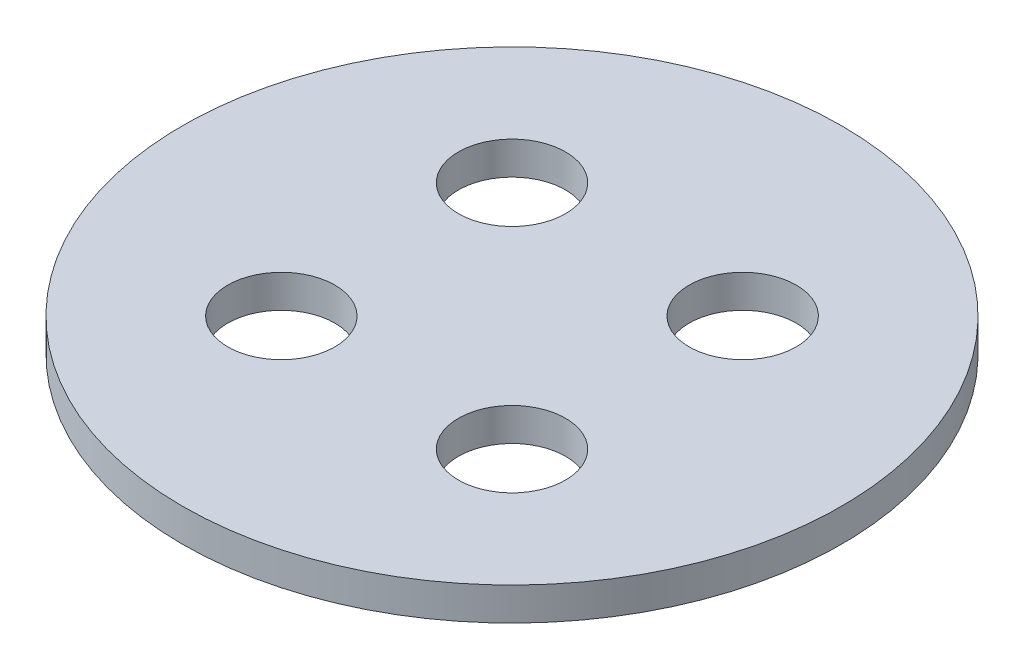
SolidWorks part; units mm, degrees
material "1023 Carbon Steel Sheet (SS)"
ref_plane "Front Plane" through (0, 0, 0) normal (0, 0, 1) x (1, 0, 0)
ref_plane "Top Plane" through (0, 0, 0) normal (0, 1, 0) x (1, 0, 0)
ref_plane "Right Plane" through (0, 0, 0) normal (1, 0, 0) x (0, 0, -1)
sketch "Sketch1" plane through (0, 0, 0) normal (0, 1, 0) x (1, 0, 0)
  line L0 (0, -55) -> (0, 55) construction
  line L1 (-55, 0) -> (55, 0) construction
  circle A0 centre (0, 0) radius 20
  circle A1 centre (-7, 7) radius 3.25
  circle A2 centre (7, 7) radius 3.25
  circle A3 centre (7, -7) radius 3.25
  circle A4 centre (-7, -7) radius 3.25
  dimension "D1" = 40
  dimension "D2" = 6.5
  dimension "D3" = 14
  dimension "D4" = 14
extrude "Boss-Extrude1" add sketch "Sketch1" along normal blind 2
